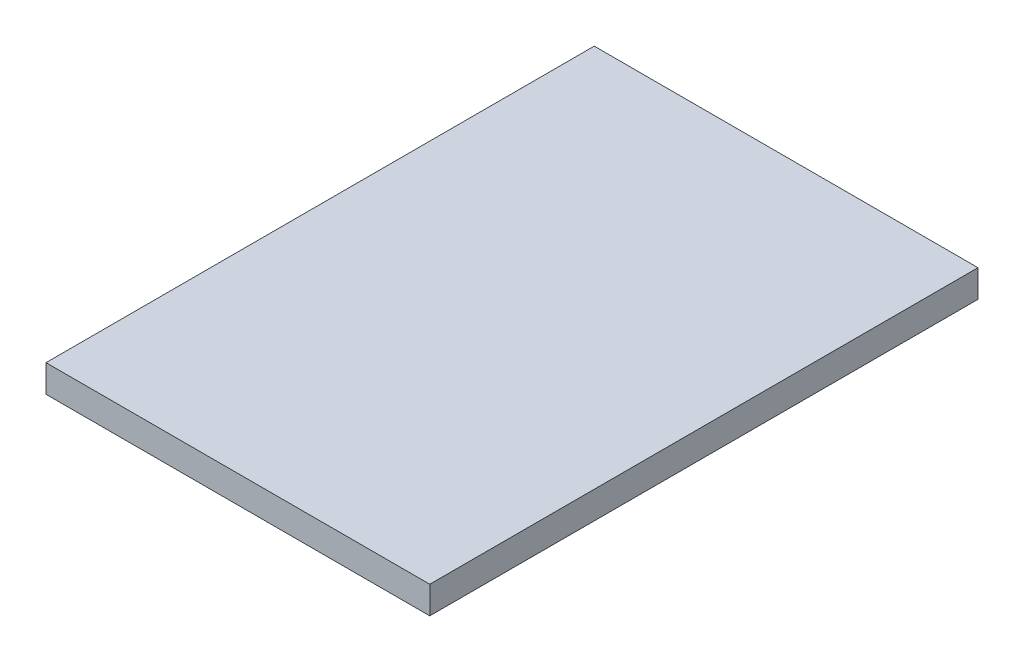
SolidWorks part; units mm, degrees
ref_plane "Front Plane" through (0, 0, 0) normal (0, 0, 1) x (1, 0, 0)
ref_plane "Top Plane" through (0, 0, 0) normal (0, 1, 0) x (1, 0, 0)
ref_plane "Right Plane" through (0, 0, 0) normal (1, 0, 0) x (0, 0, -1)
sketch "Sketch1" plane through (0, 0, 0) normal (0, 1, 0) x (1, 0, 0)
  line L1 (-2352.9011, -3118.7291) -> (1147.0989, -3118.7291)
  line L2 (-2352.9011, -3118.7291) -> (-2352.9011, 1881.2709)
  line L3 (-2352.9011, 1881.2709) -> (1147.0989, 1881.2709)
  line L4 (1147.0989, -3118.7291) -> (1147.0989, 1881.2709)
  dimension "D1" = 3500
  dimension "D2" = 5000
extrude "Boss-Extrude1" add sketch "Sketch1" along normal blind 250
